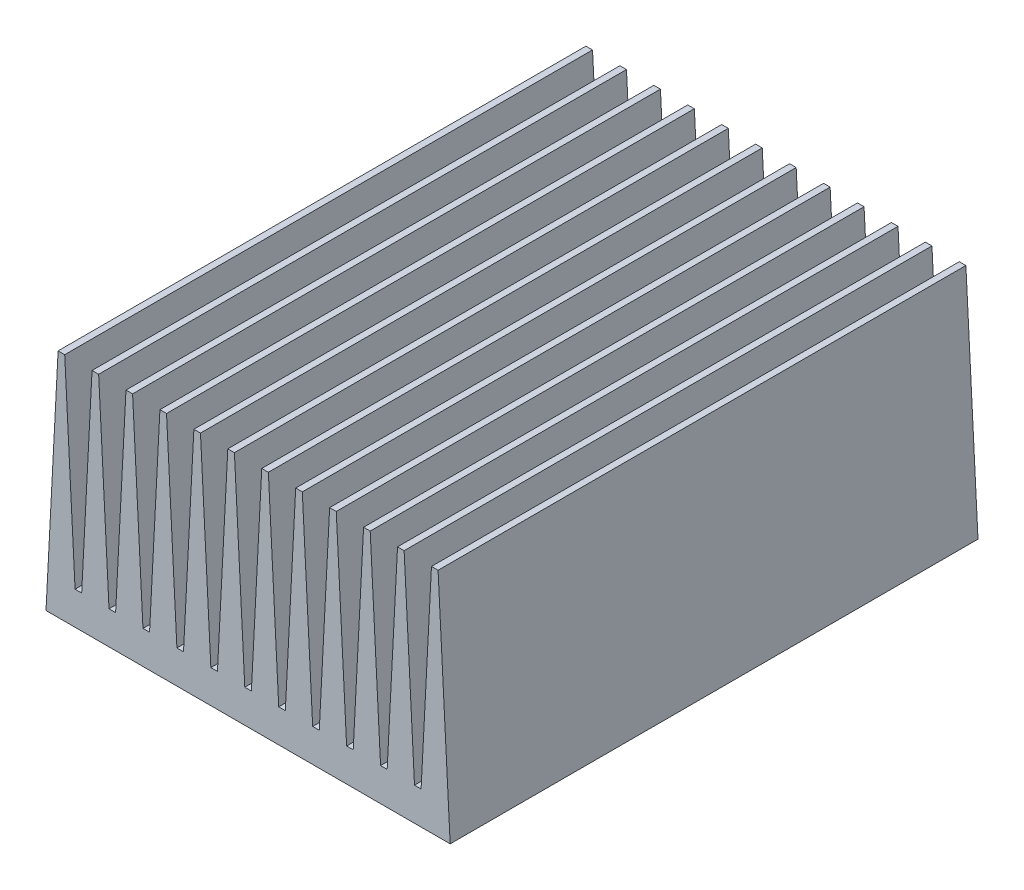
SolidWorks part; units mm, degrees
material "1060 Alloy"
ref_plane "Front Plane" through (0, 0, 0) normal (0, 0, 1) x (1, 0, 0)
ref_plane "Top Plane" through (0, 0, 0) normal (0, 1, 0) x (1, 0, 0)
ref_plane "Right Plane" through (0, 0, 0) normal (1, 0, 0) x (0, 0, -1)
sketch "Sketch1" plane through (0, 0, 0) normal (0, 0, 1) x (1, 0, 0)
  line L0 (0, 0) -> (-1.5722, 30)
  line L1 (-1.5722, 30) -> (-2.5722, 30)
  line L2 (-2.5722, 30) -> (-4.1445, 0)
  line L3 (-4.1445, 0) -> (-5.1445, 0)
  line L4 (-5.1445, 0) -> (-6.7167, 30)
  line L5 (-6.7167, 30) -> (-7.7167, 30)
  line L6 (-7.7167, 30) -> (-9.2889, 0)
  line L7 (0, 0) -> (0.262, -5)
  line L8 (0.262, -5) -> (-60.9956, -5)
  line L9 (-60.7336, 0) -> (0, 0) construction
  line L10 (-9.2889, 0) -> (0, 0) construction
  line L11 (-9.2889, 0) -> (-10.2889, 0)
  line L12 (-10.2889, 0) -> (-11.8612, 30)
  line L13 (-11.8612, 30) -> (-12.8612, 30)
  line L14 (-12.8612, 30) -> (-14.4334, 0)
  line L15 (-10.2889, 0) -> (-9.2889, 0)
  line L16 (-23.1501, 30) -> (-24.7223, 0)
  line L17 (-22.1501, 30) -> (-23.1501, 30)
  line L18 (-20.5779, 0) -> (-22.1501, 30)
  line L19 (-19.5779, 0) -> (-20.5779, 0)
  line L20 (-18.0056, 30) -> (-19.5779, 0)
  line L21 (-17.0056, 30) -> (-18.0056, 30)
  line L22 (-15.4334, 0) -> (-17.0056, 30)
  line L23 (-33.439, 30) -> (-35.0113, 0)
  line L24 (-32.439, 30) -> (-33.439, 30)
  line L25 (-30.8668, 0) -> (-32.439, 30)
  line L26 (-29.8668, 0) -> (-30.8668, 0)
  line L27 (-28.2946, 30) -> (-29.8668, 0)
  line L28 (-27.2946, 30) -> (-28.2946, 30)
  line L29 (-25.7223, 0) -> (-27.2946, 30)
  line L30 (-43.728, 30) -> (-45.3002, 0)
  line L31 (-42.728, 30) -> (-43.728, 30)
  line L32 (-41.1557, 0) -> (-42.728, 30)
  line L33 (-40.1557, 0) -> (-41.1557, 0)
  line L34 (-38.5835, 30) -> (-40.1557, 0)
  line L35 (-37.5835, 30) -> (-38.5835, 30)
  line L36 (-36.0113, 0) -> (-37.5835, 30)
  line L37 (-54.0169, 30) -> (-55.5891, 0)
  line L38 (-53.0169, 30) -> (-54.0169, 30)
  line L39 (-51.4447, 0) -> (-53.0169, 30)
  line L40 (-50.4447, 0) -> (-51.4447, 0)
  line L41 (-48.8724, 30) -> (-50.4447, 0)
  line L42 (-47.8724, 30) -> (-48.8724, 30)
  line L43 (-46.3002, 0) -> (-47.8724, 30)
  line L44 (-15.4334, 0) -> (-14.4334, 0)
  line L45 (-25.7223, 0) -> (-24.7223, 0)
  line L46 (-36.0113, 0) -> (-35.0113, 0)
  line L47 (-46.3002, 0) -> (-45.3002, 0)
  line L48 (-58.1614, 30) -> (-56.5891, 0)
  line L49 (-56.5891, 0) -> (-55.5891, 0)
  line L50 (-60.7336, 0) -> (0, 0)
  line L69 (-59.1614, 30) -> (-60.7336, 0)
  line L70 (-58.1614, 30) -> (-59.1614, 30)
  line L78 (-60.7336, 0) -> (-60.9956, -5)
  dimension "D1" = 93
  dimension "D2" = 87
  dimension "D3" = 87
  dimension "D4" = 1
  dimension "D5" = 1
  dimension "D6" = 1
  dimension "D7" = 87
  dimension "D8" = 35
  dimension "D9" = 5.0069
  dimension "D10" = 5
  dimension "D19" = 93
  dimension "D20" = 1
  dimension "D11" = 1
  dimension "D12" = 87
  dimension "D13" = 87
  dimension "D14" = 1
  dimension "D15" = 0
  dimension "D17" = 1
  dimension "D18" = 1
  dimension "D21" = 1
  dimension "D22" = 87
  dimension "D16" = 5
extrude "Boss-Extrude1" add sketch "Sketch1" along normal blind 80 contours L50 L78 L8 L7 L3 L11 L44 L19 L45 L26 L46 L33 L47 L40 L49 | L37 L50 L39 L38 | L48 L70 L69 L50 | L41 L50 L43 L42 | L30 L50 L32 L31 | L34 L50 L36 L35 | L23 L50 L25 L24 | L27 L50 L29 L28 | L16 L50 L18 L17 | L20 L50 L22 L21 | L14 L50 L12 L13 | L6 L50 L4 L5 | L2 L50 L0 L1
equation "\"A\" = 35"
equation "\"B\" = 80"
equation "\"C\"= 1"
equation "\"D4@Sketch1\"=\"C\""
equation "\"D5@Sketch1\"=\"C\""
equation "\"D6@Sketch1\"=\"C\""
equation "\"D8@Sketch1\"=\"A\""
equation "\"D11@Sketch1\"=\"C\""
equation "\"D14@Sketch1\"=\"C\""
equation "\"D17@Sketch1\"=\"C\""
equation "\"D18@Sketch1\"=\"C\""
equation "\"D21@Sketch1\"=\"C\""
equation "\"D1@Boss-Extrude1\"=\"B\""
